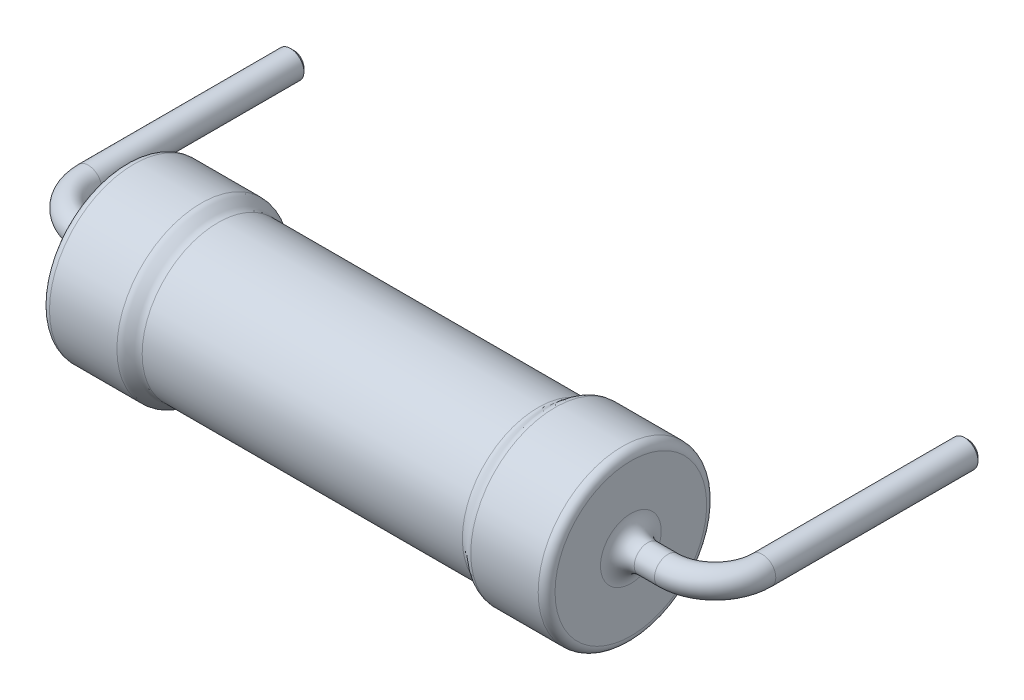
SolidWorks part; units mm, degrees
ref_plane "Спереди" through (0, 0, 0) normal (0, 0, 1) x (1, 0, 0)
ref_plane "Сверху" through (0, 0, 0) normal (0, 1, 0) x (1, 0, 0)
ref_plane "Справа" through (0, 0, 0) normal (1, 0, 0) x (0, 0, -1)
sketch "Эскиз1" plane through (0, 0, 0) normal (0, 1, 0) x (1, 0, 0)
  line L0 (0, 0) -> (0, -4.5) construction
  line L1 (-11.4563, -4.5) -> (11.4563, -4.5) construction
  line L2 (-8, -4.5) -> (8, -4.5)
  line L3 (-8, -4.5) -> (-8, -4.1)
  line L4 (-7.5, -3.6) -> (-7.5, -2.25)
  line L5 (-7.25, -2) -> (-5.25, -2)
  line L6 (-4.75, -2.25) -> (4.75, -2.25)
  line L7 (-5.25, -2) -> (-5.25, -2.25) construction
  line L8 (-5.25, -2.25) -> (-4.75, -2.25) construction
  line L9 (-5, -2.125) -> (-5.25, -2.125) construction
  line L10 (-5, -2.125) -> (-5, -2.25) construction
  line L11 (8, -4.5) -> (8, -4.1)
  line L12 (7.5, -3.6) -> (7.5, -2.25)
  line L13 (7.25, -2) -> (5.25, -2)
  arc A0 (-8, -4.1) -> (-7.5, -3.6) centre (-8, -3.6) ccw
  arc A1 (-7.5, -2.25) -> (-7.25, -2) centre (-7.25, -2.25) cw
  arc A2 (8, -4.1) -> (7.5, -3.6) centre (8, -3.6) cw
  arc A3 (7.5, -2.25) -> (7.25, -2) centre (7.25, -2.25) ccw
  spline S0 degree 3 poles (-5.25, -2) (-5.1385, -2) (-5.0012, -2.125) (-4.8591, -2.25) (-4.75, -2.25) knots 0 0 0 0 0.5 1 1 1 1
  spline S1 degree 3 poles (5.25, -2) (5.1385, -2) (5.0012, -2.125) (4.8591, -2.25) (4.75, -2.25) knots 0 0 0 0 0.5 1 1 1 1
  point P5 (0, -4.5)
  point P25 (0, -2.25)
  point P26 (-7.5, -2.925)
  dimension "D4" = 0.5
  dimension "D5" = 0.25
  dimension "D1" = 0.8
  dimension "D2" = 15
  dimension "D3" = 5
  dimension "D6" = 2
  dimension "D7" = 9.5
  dimension "D8" = 4.5
  dimension "D9" = 2
  dimension "D10" = 16
revolve "Повернуть1" add sketch "Эскиз1" angle 360 about L1
sketch "Эскиз2" plane through (0, 0, 0) normal (0, 1, 0) x (1, 0, 0)
  line L0 (-8, -4.5) -> (-8.6, -4.5)
  line L1 (-10, -3.1) -> (-10, 3)
  line L4 (-8, -4.1) -> (-8, -4.9) construction
  line L5 (-8, -4.1) -> (-8.6, -4.1) construction
  line L6 (0, 0) -> (0, 2.5025) construction
  arc A0 (-8.6, -4.5) -> (-10, -3.1) centre (-8.6, -3.1) cw
  arc A1 (-8.6, -4.1) -> (-9.6, -3.1089) centre (-8.6, -3.1) cw construction
  dimension "D1" = 1
  dimension "D2" = 3
  dimension "D3" = 20
sketch "Эскиз3" plane through (-8, 0, 0) normal (-1, 0, 0) x (0, 0, 1)
  line L0 (4.1, 0) -> (4.9, 0) construction
  circle A0 centre (4.5, 0) radius 0.4
sweep "По траектории1" add profiles "Эскиз3" path "Эскиз2"
chamfer "Фаска1" distance 0.1 angle 45 1 edges at (-10.4, 0, -3)
mirror "Зеркальное отражение1" about plane through (0, 0, 0) normal (1, 0, 0) of "По траектории1", "Фаска1"
